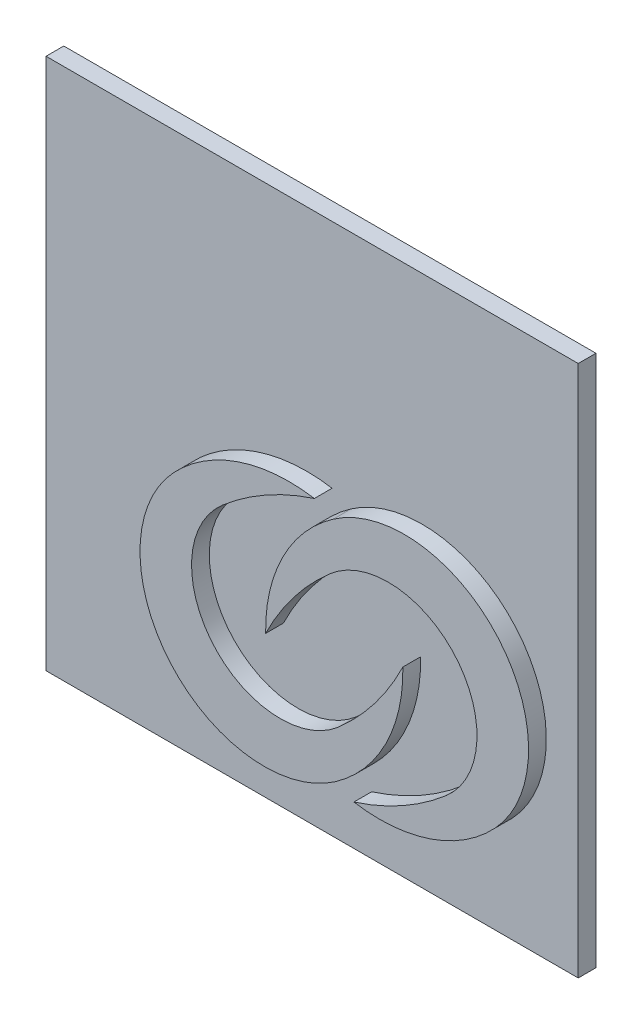
SolidWorks part; units mm, degrees
material "Obyčejná uhlíková ocel"
ref_plane "Přední rovina" through (0, 0, 0) normal (0, 0, 1) x (1, 0, 0)
ref_plane "Horní rovina" through (0, 0, 0) normal (0, 1, 0) x (1, 0, 0)
ref_plane "Pravá rovina" through (0, 0, 0) normal (1, 0, 0) x (0, 0, -1)
sketch "Skica1" plane through (0, 0, 0) normal (0, 0, 1) x (1, 0, 0)
  line L1 (0, 0) -> (300, 0)
  line L2 (0, 0) -> (0, 300)
  line L3 (0, 300) -> (300, 300)
  line L4 (300, 0) -> (300, 300)
  dimension "D1" = 300
extrude "Přidat vysunutím1" add sketch "Skica1" along normal blind 10
sketch "Skica3" plane through (0, 0, 10) normal (0, 0, 1) x (1, 0, 0)
  line L21 (80.1577, 48.8264) -> (134.223, 95.8532) construction
  line L26 (81.7478, 142.4914) -> (134.223, 95.8532) construction
  line L27 (134.223, 95.8532) -> (173.1393, 37.4214) construction
  line L28 (134.223, 95.8532) -> (211.136, 112.3896) construction
  line L29 (161.2582, 169.7325) -> (134.223, 95.8532) construction
  line L30 (134.223, 95.8532) -> (109.3071, 140.4488) construction
  line L31 (174.9355, 64.9978) -> (134.223, 95.8532) construction
  line L32 (124.5422, 199.0828) -> (231.4757, 75.8503) construction
  line L33 (300, 0) -> (270.288, -139.0795) construction
  line L34 (161.2582, 169.7325) -> (211.4558, 111.8837) construction
  arc A30 (161.2582, 169.7325) -> (81.7478, 142.4914) centre (146.9847, 81.737) ccw
  arc A31 (81.7478, 142.4914) -> (173.1393, 37.4214) centre (132.9841, 94.7756) ccw
  arc A32 (173.1393, 37.4214) -> (211.136, 112.3896) centre (122.0114, 110.448) ccw
  arc A37 (109.3071, 140.4488) -> (174.9355, 64.9978) centre (142.0277, 102.6419) ccw
  arc A38 (109.3071, 140.4488) -> (161.2582, 169.7325) centre (207.4689, 27.028) cw
  arc A39 (174.9355, 64.9978) -> (211.136, 112.3896) centre (76.2121, 177.93) ccw
  arc A40 (250.1876, 130.2969) -> (198.1673, 101.1362) centre (152.2946, 243.9497) cw construction
  arc A41 (277.742, 128.189) -> (198.1673, 101.1362) centre (212.6491, 189.0978) cw construction
  arc A42 (184.738, 205.903) -> (250.1876, 130.2969) centre (217.5566, 168.1812) cw construction
  arc A43 (186.5995, 233.4752) -> (277.742, 128.189) centre (226.6188, 176.026) cw construction
  arc A44 (148.4255, 158.5971) -> (186.5995, 233.4752) centre (237.5543, 160.3277) cw construction
  arc A45 (184.738, 205.903) -> (148.4255, 158.5971) centre (283.1938, 92.7375) ccw construction
  arc A46 (263.1177, 59.7337) -> (183.543, 32.6809) centre (198.0248, 120.6424) cw
  arc A47 (235.5633, 61.8416) -> (183.543, 32.6809) centre (137.6703, 175.4944) cw
  arc A48 (170.1137, 137.4477) -> (235.5633, 61.8416) centre (202.9323, 99.7259) cw
  arc A49 (171.9751, 165.0199) -> (263.1177, 59.7337) centre (211.9945, 107.5707) cw
  arc A50 (133.8011, 90.1418) -> (171.9751, 165.0199) centre (222.93, 91.8724) cw
  arc A51 (170.1137, 137.4477) -> (133.8011, 90.1418) centre (268.5695, 24.2821) ccw
  point P13 (104.3021, 69.8276)
  point P19 (193.4445, 127.0458)
  point P34 (394.5714, -31.9905)
  point P35 (308.6141, -110.8907)
  point P36 (258.8811, -105.6301)
  point P37 (295.047, -111.5815)
  point P50 (247.0834, -101.0521)
  point P51 (258.8811, -134.4713)
  point P52 (270.288, -139.0795)
  dimension "D1" = 50
  dimension "D2" = 150
  dimension "D3" = 32
  dimension "D4" = 115
  dimension "D5" = 38
  dimension "D6" = 100
  dimension "D7" = 2
  dimension "D8" = 70
extrude "Přidat vysunutím3" add sketch "Skica3" along normal blind 10
